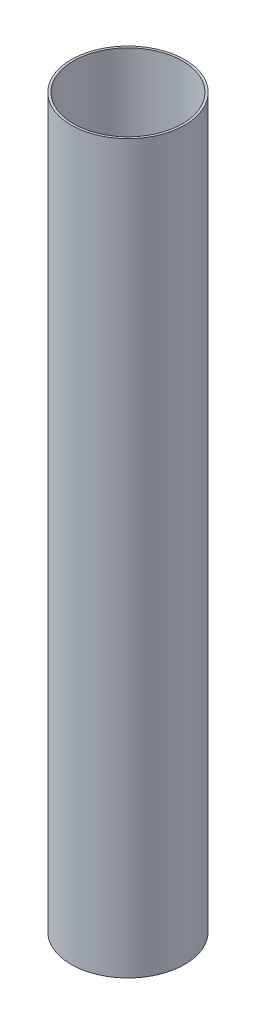
SolidWorks part; units mm, degrees
ref_plane "Front Plane" through (0, 0, 0) normal (0, 0, 1) x (1, 0, 0)
ref_plane "Top Plane" through (0, 0, 0) normal (0, 1, 0) x (1, 0, 0)
ref_plane "Right Plane" through (0, 0, 0) normal (1, 0, 0) x (0, 0, -1)
sketch "Sketch2" plane through (0, 0, 0) normal (0, 1, 0) x (1, 0, 0)
  circle A0 centre (0, 0) radius 38.1
  circle A1 centre (0, 0) radius 39.6748
  dimension "D1" = 76.2
  dimension "D2" = 79.3496
extrude "Boss-Extrude1" add sketch "Sketch2" along normal mid plane 508
equation "\"airframeInnerDiameter\"=3"
equation "\"outerDiameter\"=3.124"
equation "\"payloadAirframeLength\"= 5"
equation "\"lowerAirframeLength\"=20"
equation "\"D1@Sketch2\"=\"airframeInnerDiameter\""
equation "\"D2@Sketch2\"=\"outerDiameter\""
equation "\"D1@Boss-Extrude1\"=\"lowerAirframeLength\""
